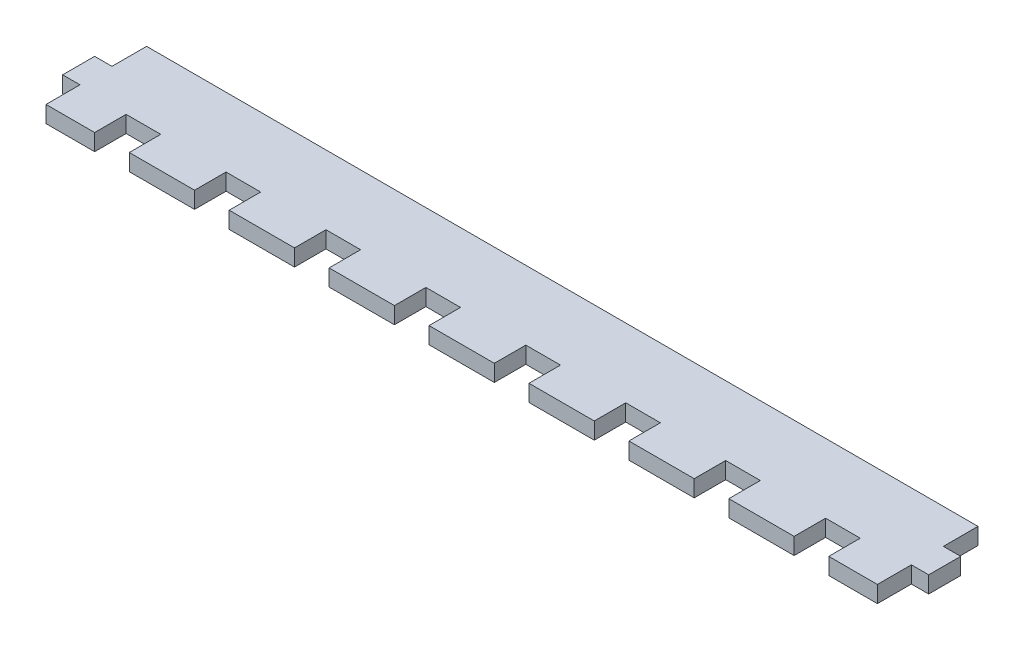
SolidWorks part; units mm, degrees
ref_plane "Front Plane" through (0, 0, 0) normal (0, 0, 1) x (1, 0, 0)
ref_plane "Top Plane" through (0, 0, 0) normal (0, 1, 0) x (1, 0, 0)
ref_plane "Right Plane" through (0, 0, 0) normal (1, 0, 0) x (0, 0, -1)
sketch "Sketch1" plane through (0, 0, 0) normal (0, 1, 0) x (1, 0, 0)
  line L2 (-165.1, -28.575) -> (-165.1, 28.575)
  line L3 (-165.1, 28.575) -> (165.1, 28.575)
  line L4 (165.1, -28.575) -> (165.1, 28.575)
  line L5 (-165.1, -28.575) -> (165.1, 28.575) construction
  line L6 (-165.1, 28.575) -> (165.1, -28.575) construction
  line L11 (-165.1, -28.575) -> (165.1, -28.575)
  point P0 (0, 0)
  dimension "D1" = 57.15
  dimension "D2" = 330.2
extrude "Boss-Extrude1" add sketch "Sketch1" along normal blind 6.35
sketch "Sketch3" plane through (0, 0, 0) normal (0, 1, 0) x (1, 0, 0)
  line L0 (-165.1, -28.575) -> (165.1, -28.575) construction
  line L1 (-126.746, -28.575) -> (-126.746, -40.575)
  line L2 (-126.746, -40.575) -> (-101.854, -40.575)
  line L3 (-101.854, -40.575) -> (-101.854, -28.575)
  line L4 (-101.854, -28.575) -> (-126.746, -28.575)
  line L25 (-63.754, -40.575) -> (-63.754, -28.575)
  line L26 (-63.754, -28.575) -> (-88.646, -28.575)
  line L27 (-88.646, -28.575) -> (-88.646, -40.575)
  line L28 (-88.646, -40.575) -> (-63.754, -40.575)
  line L29 (-25.654, -40.575) -> (-25.654, -28.575)
  line L30 (-25.654, -28.575) -> (-50.546, -28.575)
  line L31 (-50.546, -28.575) -> (-50.546, -40.575)
  line L32 (-50.546, -40.575) -> (-25.654, -40.575)
  line L33 (12.446, -40.575) -> (12.446, -28.575)
  line L34 (12.446, -28.575) -> (-12.446, -28.575)
  line L35 (-12.446, -28.575) -> (-12.446, -40.575)
  line L36 (-12.446, -40.575) -> (12.446, -40.575)
  line L37 (50.546, -40.575) -> (50.546, -28.575)
  line L38 (50.546, -28.575) -> (25.654, -28.575)
  line L39 (25.654, -28.575) -> (25.654, -40.575)
  line L40 (25.654, -40.575) -> (50.546, -40.575)
  line L41 (88.646, -40.575) -> (88.646, -28.575)
  line L42 (88.646, -28.575) -> (63.754, -28.575)
  line L43 (63.754, -28.575) -> (63.754, -40.575)
  line L44 (63.754, -40.575) -> (88.646, -40.575)
  line L45 (126.746, -40.575) -> (126.746, -28.575)
  line L46 (126.746, -28.575) -> (101.854, -28.575)
  line L47 (101.854, -28.575) -> (101.854, -40.575)
  line L48 (101.854, -40.575) -> (126.746, -40.575)
  line L49 (164.846, -40.575) -> (164.846, -28.575)
  line L50 (164.846, -28.575) -> (139.954, -28.575)
  line L51 (139.954, -28.575) -> (139.954, -40.575)
  line L52 (139.954, -40.575) -> (164.846, -40.575)
  line L53 (-164.846, -28.575) -> (-164.846, -40.575)
  line L54 (-164.846, -40.575) -> (-139.954, -40.575)
  line L55 (-139.954, -40.575) -> (-139.954, -28.575)
  line L56 (-139.954, -28.575) -> (-164.846, -28.575)
  point P0 (-114.3, -28.575)
  point P37 (-152.4, -28.575)
  dimension "D1" = 24.892
  dimension "D2" = 12
  dimension "D3" = 50.8
  dimension "D4" = 8
  dimension "D5" = 2
extrude "Boss-Extrude2" add sketch "Sketch3" along normal blind 6.35
sketch "Sketch4" plane through (0, 0, 0) normal (0, 1, 0) x (1, 0, 0)
  line L0 (165.1, 28.575) -> (-165.1, 28.575) construction
  line L8 (0, 0) -> (0, 58.9975) construction
  line L13 (165.1, -28.575) -> (165.1, 28.575) construction
  line L14 (158.496, 23.179) -> (171.704, 23.179)
  line L30 (158.496, 23.179) -> (158.496, 9.971)
  line L31 (158.496, 9.971) -> (171.704, 9.971)
  line L32 (171.704, 23.179) -> (171.704, 9.971)
  line L33 (158.496, 23.179) -> (171.704, 9.971) construction
  line L34 (158.496, 9.971) -> (171.704, 23.179) construction
  line L35 (-158.496, -40.829) -> (-171.704, -27.621) construction
  line L38 (-158.496, -27.621) -> (-171.704, -40.829) construction
  line L39 (-158.496, -15.429) -> (-171.704, -2.221) construction
  line L44 (-158.496, -2.221) -> (-171.704, -15.429) construction
  line L45 (-158.496, 9.971) -> (-171.704, 23.179) construction
  line L50 (-158.496, 23.179) -> (-171.704, 9.971) construction
  line L51 (-171.704, -27.621) -> (-171.704, -40.829)
  line L52 (158.496, -2.221) -> (171.704, -2.221)
  line L53 (158.496, -2.221) -> (158.496, -15.429)
  line L54 (158.496, -15.429) -> (171.704, -15.429)
  line L55 (171.704, -2.221) -> (171.704, -15.429)
  line L56 (158.496, -2.221) -> (171.704, -15.429) construction
  line L57 (158.496, -15.429) -> (171.704, -2.221) construction
  line L58 (158.496, -27.621) -> (171.704, -27.621)
  line L59 (158.496, -27.621) -> (158.496, -40.829)
  line L60 (158.496, -40.829) -> (171.704, -40.829)
  line L61 (171.704, -27.621) -> (171.704, -40.829)
  line L62 (158.496, -27.621) -> (171.704, -40.829) construction
  line L63 (158.496, -40.829) -> (171.704, -27.621) construction
  line L64 (-108.204, 23.179) -> (-94.996, 23.179) [skipped]
  line L65 (-108.204, 23.179) -> (-108.204, 9.971) [skipped]
  line L66 (-108.204, 9.971) -> (-94.996, 9.971) [skipped]
  line L67 (-94.996, 23.179) -> (-94.996, 9.971) [skipped]
  line L68 (-108.204, -2.221) -> (-94.996, -2.221) [skipped]
  line L69 (-108.204, -2.221) -> (-108.204, -15.429) [skipped]
  line L70 (-108.204, -15.429) -> (-94.996, -15.429) [skipped]
  line L71 (-94.996, -2.221) -> (-94.996, -15.429) [skipped]
  line L72 (-108.204, -27.621) -> (-94.996, -27.621) [skipped]
  line L73 (-108.204, -27.621) -> (-108.204, -40.829) [skipped]
  line L74 (-108.204, -40.829) -> (-94.996, -40.829) [skipped]
  line L75 (-94.996, -27.621) -> (-94.996, -40.829) [skipped]
  line L76 (-108.204, 23.179) -> (-94.996, 9.971) construction
  line L77 (-108.204, 9.971) -> (-94.996, 23.179) construction
  line L78 (-108.204, -2.221) -> (-94.996, -15.429) construction
  line L79 (-108.204, -15.429) -> (-94.996, -2.221) construction
  line L80 (-108.204, -27.621) -> (-94.996, -40.829) construction
  line L81 (-108.204, -40.829) -> (-94.996, -27.621) construction
  line L82 (-158.496, -40.829) -> (-171.704, -40.829)
  line L83 (-158.496, -27.621) -> (-158.496, -40.829)
  line L84 (-158.496, -27.621) -> (-171.704, -27.621)
  line L85 (-171.704, -2.221) -> (-171.704, -15.429)
  line L86 (-158.496, -15.429) -> (-171.704, -15.429)
  line L87 (-158.496, -2.221) -> (-158.496, -15.429)
  line L88 (-158.496, -2.221) -> (-171.704, -2.221)
  line L89 (-171.704, 23.179) -> (-171.704, 9.971)
  line L90 (-158.496, 9.971) -> (-171.704, 9.971)
  line L91 (-158.496, 23.179) -> (-158.496, 9.971)
  line L92 (-158.496, 23.179) -> (-171.704, 23.179)
  point P0 (-101.6, -34.225)
  point P1 (-101.6, -8.825)
  point P5 (-101.6, 16.575)
  point P13 (165.1, 16.575)
  point P27 (-165.1, -34.225)
  point P28 (-165.1, -8.825)
  point P29 (165.1, -8.825)
  point P34 (165.1, -34.225)
  point P36 (-165.1, 16.575)
  dimension "D1" = 3
  dimension "D2" = 2
  dimension "D4" = 13.208
  dimension "D6" = 13.208
  dimension "D7" = 12
extrude "Cut-Extrude2" cut sketch "Sketch4" along normal through all
sketch "Sketch5" plane through (0, 0, -28.575) normal (0, 0, -1) x (-1, 0, 0)
  line L1 (177.8338, -17.2087) -> (-187.511, -17.2087)
  line L2 (177.8338, -17.2087) -> (177.8338, 19.7789)
  line L3 (177.8338, 19.7789) -> (-187.511, 19.7789)
  line L4 (-187.511, -17.2087) -> (-187.511, 19.7789)
extrude "Cut-Extrude3" cut sketch "Sketch5" against normal up to surface (30.796 mm away) up to face at (-161.798, 3.175, 2.221)
